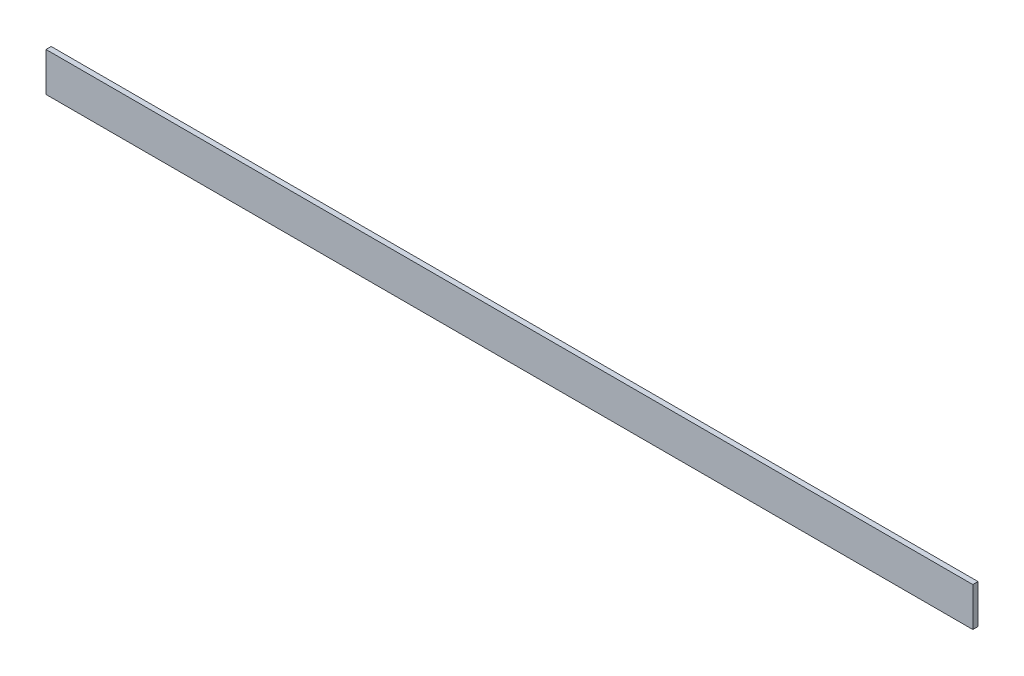
SolidWorks part; units mm, degrees
material "ASTM A36 Steel"
ref_plane "Front Plane" through (0, 0, 0) normal (0, 0, 1) x (1, 0, 0)
ref_plane "Top Plane" through (0, 0, 0) normal (0, 1, 0) x (1, 0, 0)
ref_plane "Right Plane" through (0, 0, 0) normal (1, 0, 0) x (0, 0, -1)
sketch "Sketch1" plane through (0, 0, 0) normal (0, 0, 1) x (1, 0, 0)
  line L1 (-356.76, -15) -> (356.76, -15)
  line L2 (-356.76, -15) -> (-356.76, 15)
  line L3 (-356.76, 15) -> (356.76, 15)
  line L4 (356.76, -15) -> (356.76, 15)
  line L5 (-356.76, -15) -> (356.76, 15) construction
  line L6 (-356.76, 15) -> (356.76, -15) construction
  point P0 (0, 0)
  dimension "D1" = 30
  dimension "D2" = 713.52
extrude "Boss-Extrude1" add sketch "Sketch1" along normal blind 4
